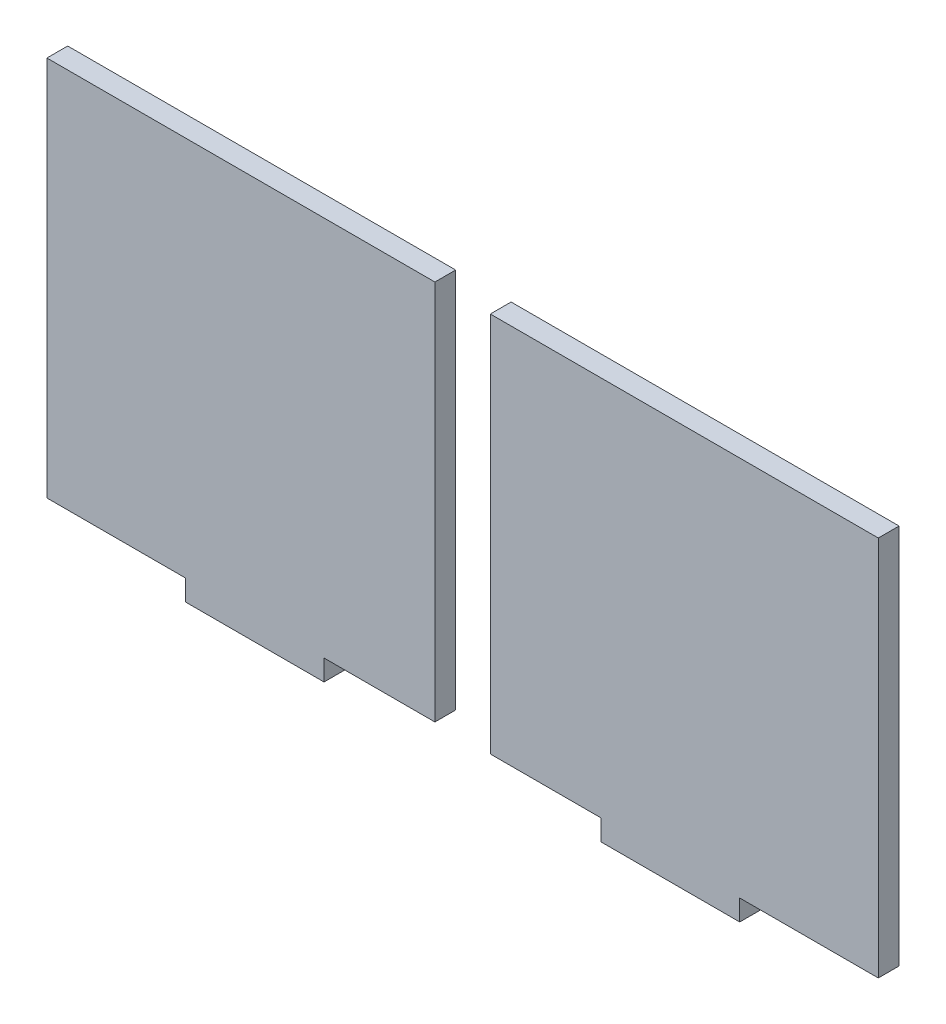
SolidWorks part; units mm, degrees
material "Acrylic (Medium-high impact)"
ref_plane "Front Plane" through (0, 0, 0) normal (0, 0, 1) x (1, 0, 0)
ref_plane "Top Plane" through (0, 0, 0) normal (0, 1, 0) x (1, 0, 0)
ref_plane "Right Plane" through (0, 0, 0) normal (1, 0, 0) x (0, 0, -1)
sketch "Sketch1" plane through (0, 0, 0) normal (0, 0, 1) x (1, 0, 0)
  line L1 (0, 0) -> (120, 0) construction
  line L2 (0, 0) -> (0, 55) construction
  line L3 (0, 55) -> (120, 55) construction
  line L4 (120, 0) -> (120, 55) construction
  line L5 (0, 0) -> (56, 0)
  line L6 (0, 0) -> (0, 55)
  line L7 (0, 55) -> (56, 55)
  line L8 (56, 0) -> (56, 55)
  line L9 (120, 55) -> (64, 55)
  line L10 (120, 55) -> (120, 0)
  line L11 (120, 0) -> (64, 0)
  line L12 (64, 55) -> (64, 0)
  dimension "D1" = 55
  dimension "D2" = 120
  dimension "D3" = 8
  dimension "D4" = 56
extrude "Boss-Extrude1" add sketch "Sketch1" against normal blind 3
sketch "Sketch2" plane through (0, 0, 0) normal (0, 0, 1) x (1, 0, 0)
  line L0 (0, 0) -> (56, 0) construction
  line L1 (20, 0) -> (40, 0)
  line L2 (20, 0) -> (20, -3)
  line L3 (20, -3) -> (40, -3)
  line L4 (40, 0) -> (40, -3)
  line L5 (64, 0) -> (120, 0) construction
  line L6 (80, 0) -> (100, 0)
  line L7 (80, 0) -> (80, -3)
  line L8 (80, -3) -> (100, -3)
  line L9 (100, 0) -> (100, -3)
  point P15 (0, 0)
  dimension "D1" = 3
  dimension "D2" = 20
  dimension "D3" = 20
  dimension "D4" = 3
  dimension "D5" = 20
  dimension "D6" = 20
extrude "Boss-Extrude2" add sketch "Sketch2" against normal blind 3
